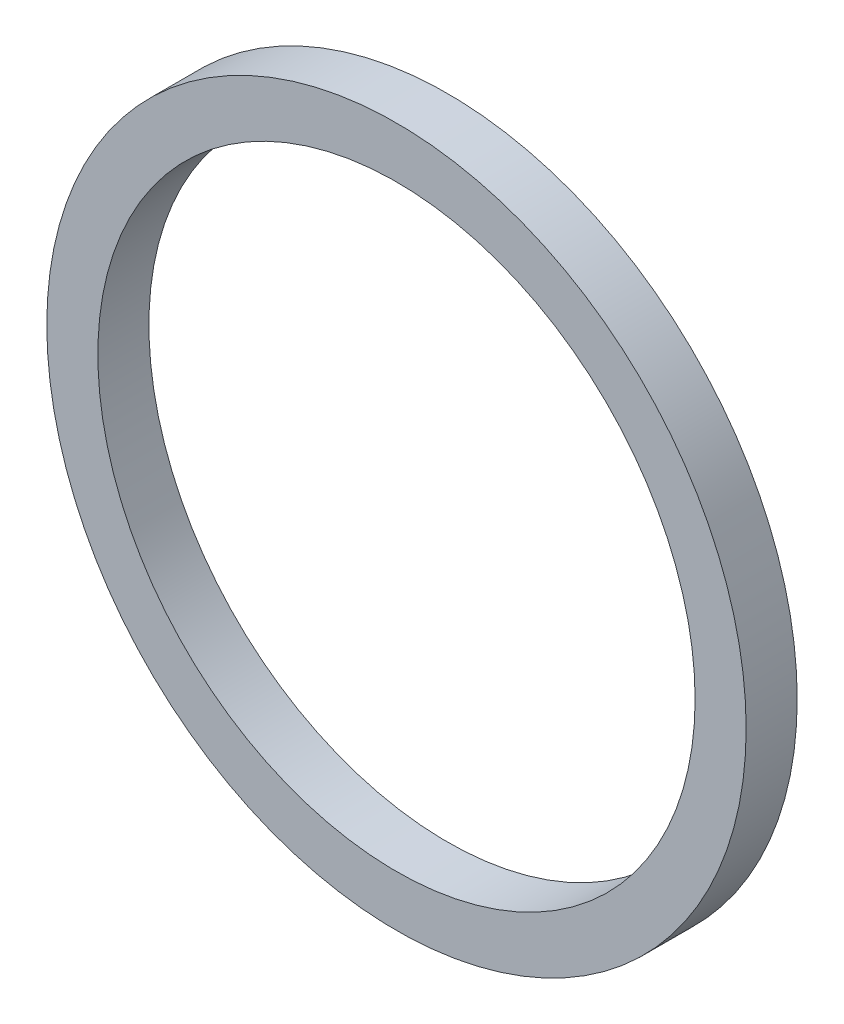
SolidWorks part; units mm, degrees
ref_plane "Plan1" through (0, 0, 0) normal (0, 0, 1) x (1, 0, 0)
ref_plane "Plan2" through (0, 0, 0) normal (0, 1, 0) x (1, 0, 0)
ref_plane "Plan3" through (0, 0, 0) normal (1, 0, 0) x (0, 0, -1)
sketch "Esquisse1" plane through (0, 0, 0) normal (0, 0, 1) x (1, 0, 0)
  circle A0 centre (0, 0) radius 13.7
  circle A1 centre (0, 0) radius 11.7
  circle A2 centre (0, 0) radius 11.7 construction
  circle A3 centre (0, 0) radius 13.7 construction
extrude "Base-Extrusion" add sketch "Esquisse1" along normal blind 2
